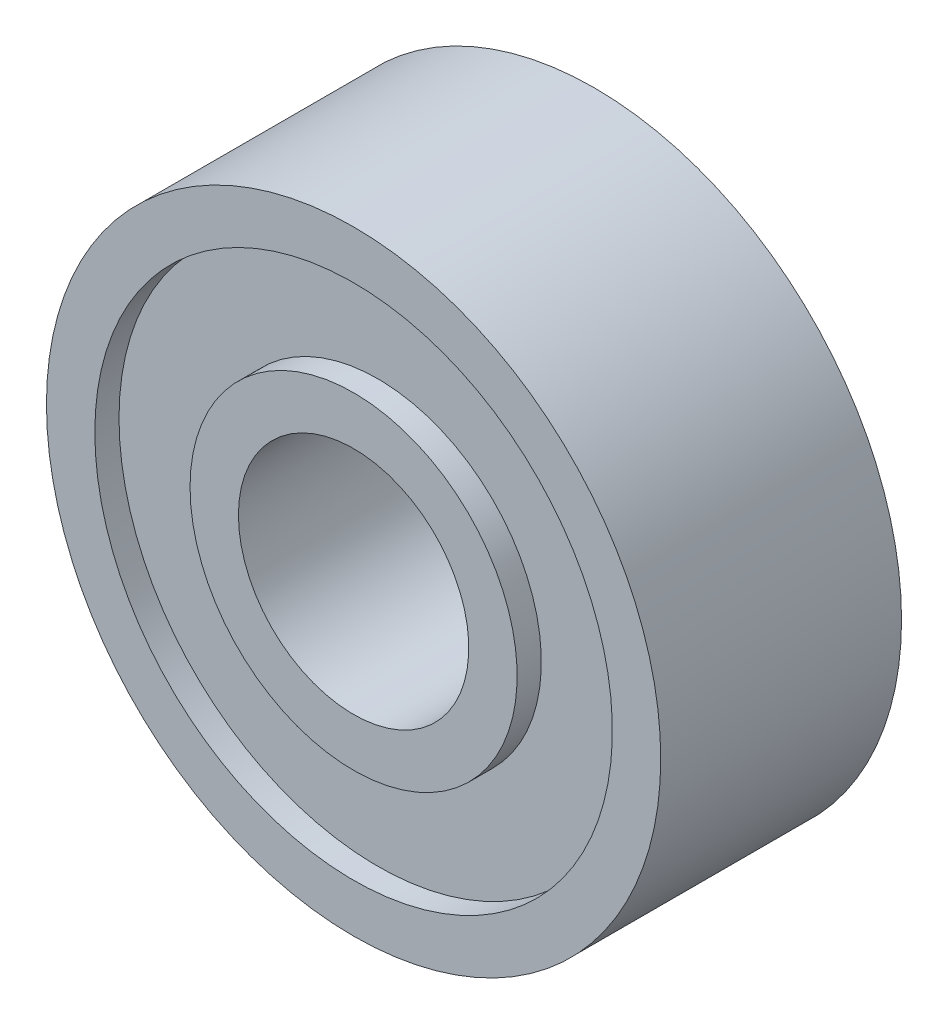
SolidWorks part; units mm, degrees
material "Plain Carbon Steel"
ref_plane "Front Plane" through (0, 0, 0) normal (0, 0, 1) x (1, 0, 0)
ref_plane "Top Plane" through (0, 0, 0) normal (0, 1, 0) x (1, 0, 0)
ref_plane "Right Plane" through (0, 0, 0) normal (1, 0, 0) x (0, 0, -1)
ref_plane "Plane4" through (0, 0, 0) normal (0, -1, 0) x (1, 0, 0)
sketch "Sketch1" plane through (0, 0, 0) normal (0, -1, 0) x (1, 0, 0)
  line L0 (3.3812, 2.4892) -> (2.3812, 2.4892)
  line L1 (2.3812, 2.4892) -> (2.3812, -2.4892)
  line L2 (2.3812, -2.4892) -> (3.3812, -2.4892)
  line L3 (3.3812, -2.4892) -> (3.3812, -1.9892)
  line L4 (3.3812, -1.9892) -> (5.35, -1.9892)
  line L5 (5.35, -1.9892) -> (5.35, -2.4892)
  line L6 (5.35, -2.4892) -> (6.35, -2.4892)
  line L7 (6.35, -2.4892) -> (6.35, 2.4892)
  line L8 (6.35, 2.4892) -> (5.35, 2.4892)
  line L9 (5.35, 2.4892) -> (5.35, 1.9892)
  line L10 (5.35, 1.9892) -> (3.3812, 1.9892)
  line L11 (3.3812, 1.9892) -> (3.3812, 2.4892)
  line L12 (0, 2.4892) -> (0, -2.4892) construction
revolve "Revolve1" add sketch "Sketch1" angle 360 about L12
